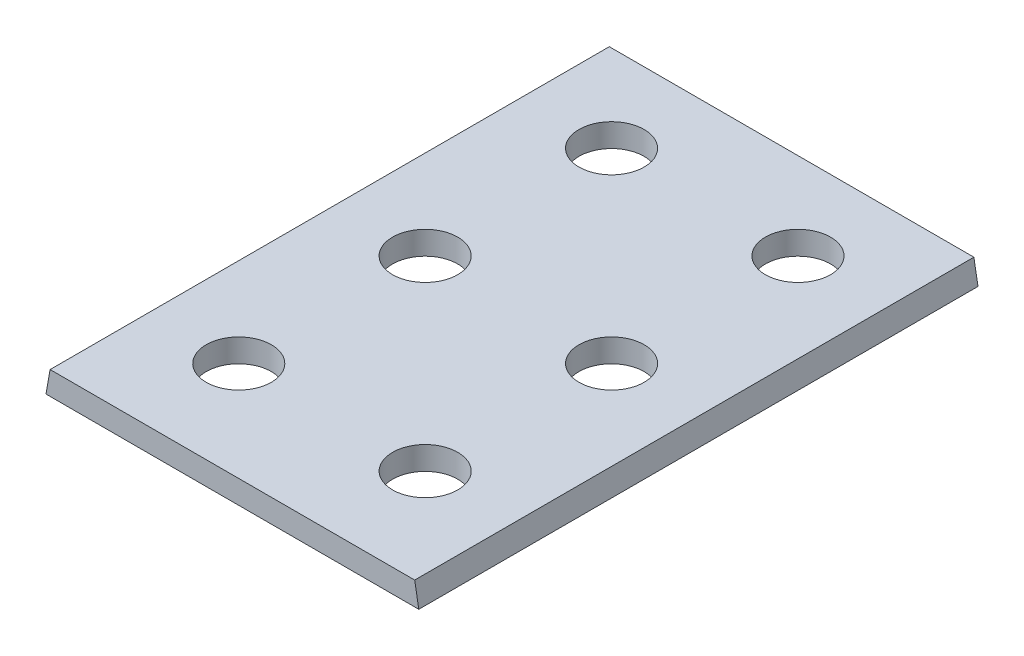
SolidWorks part; units mm, degrees
ref_plane "Front Plane" through (0, 0, 0) normal (0, 0, 1) x (1, 0, 0)
ref_plane "Top Plane" through (0, 0, 0) normal (0, 1, 0) x (1, 0, 0)
ref_plane "Right Plane" through (0, 0, 0) normal (1, 0, 0) x (0, 0, -1)
sketch "Sketch1" plane through (0, 0, 0) normal (0, 1, 0) x (1, 0, 0)
  line L1 (0, 0) -> (108, 0)
  line L2 (0, 0) -> (0, -162)
  line L3 (0, -162) -> (108, -162)
  line L4 (108, 0) -> (108, -162)
  circle A0 centre (27, -133.1561) radius 9.4381
  circle A1 centre (81, -133.1561) radius 9.4381
  circle A2 centre (81, -79.1561) radius 9.4381
  circle A3 centre (81, -25.1561) radius 9.4381
  circle A4 centre (27, -79.1561) radius 9.4381
  circle A5 centre (27, -25.1561) radius 9.4381
  dimension "D1" = 162
  dimension "D2" = 108
  dimension "D5" = 27
  dimension "D3" = 2
  dimension "D4" = 3
extrude "Boss-Extrude1" add sketch "Sketch1" along normal blind 6.75
sketch "Sketch2" plane through (0, 0, 0) normal (0, 0, 1) x (1, 0, 0)
  line L0 (0, 6.75) -> (0, 0)
  line L1 (0, 0) -> (1.1902, 6.75)
  line L2 (0, 6.75) -> (108, 6.75) construction
  line L3 (0, 6.75) -> (1.1902, 6.75)
  line L4 (108, 6.75) -> (108, 0)
  line L5 (0, 0) -> (108, 0) construction
  line L6 (108, 6.75) -> (108, 0) construction
  line L7 (108, 0) -> (106.8098, 6.75)
  line L8 (106.8098, 6.75) -> (108, 6.75)
  dimension "D1" = 10
  dimension "D2" = 10
extrude "Cut-Extrude16" cut sketch "Sketch2" against normal blind 6.75 and the other way blind 500
sketch "Sketch4" plane through (0, 6.75, 0) normal (0, 1, 0) x (1, 0, 0)
